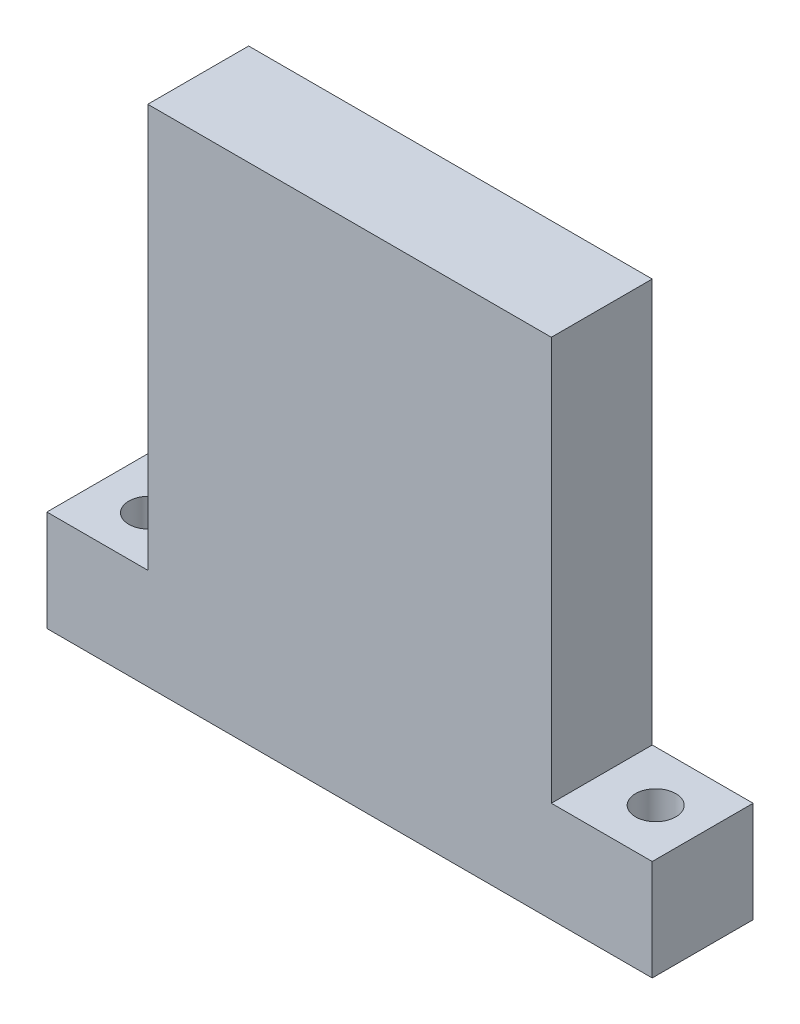
SolidWorks part; units mm, degrees
ref_plane "Front Plane" through (0, 0, 0) normal (0, 0, 1) x (1, 0, 0)
ref_plane "Top Plane" through (0, 0, 0) normal (0, 1, 0) x (1, 0, 0)
ref_plane "Right Plane" through (0, 0, 0) normal (1, 0, 0) x (0, 0, -1)
sketch "Sketch1" plane through (0, 0, 0) normal (0, 1, 0) x (1, 0, 0)
  line L1 (-30, 5) -> (30, 5)
  line L2 (-30, 5) -> (-30, -5)
  line L3 (-30, -5) -> (30, -5)
  line L4 (30, 5) -> (30, -5)
  line L5 (-30, 5) -> (30, -5) construction
  line L6 (-30, -5) -> (30, 5) construction
  point P0 (0, 0)
  dimension "D1" = 10
  dimension "D2" = 60
extrude "Boss-Extrude1" add sketch "Sketch1" along normal blind 10
sketch "Sketch2" plane through (0, 10, 0) normal (0, 1, 0) x (1, 0, 0)
  line L0 (-30, -5) -> (30, -5) construction
  line L1 (-20, 5) -> (20, 5)
  line L2 (-20, 5) -> (-20, -5)
  line L3 (-20, -5) -> (20, -5)
  line L4 (20, 5) -> (20, -5)
  line L5 (-20, 5) -> (20, -5) construction
  line L6 (-20, -5) -> (20, 5) construction
  point P0 (0, 0)
  dimension "D1" = 40
extrude "Boss-Extrude2" add sketch "Sketch2" along normal blind 40
sketch "Sketch3" plane through (0, 0, -5) normal (0, 0, -1) x (-1, 0, 0)
  line L0 (0, 0) -> (0, 30) construction
  circle A0 centre (0, 30) radius 11
  dimension "D1" = 22
extrude "Cut-Extrude1" cut sketch "Sketch3" against normal blind 8 contours A0
sketch "Sketch5" plane through (0, 10, 0) normal (0, 1, 0) x (1, 0, 0)
  circle A0 centre (-24.8797, 0) radius 2
  circle A1 centre (25.343, 0) radius 2
extrude "Cut-Extrude2" cut sketch "Sketch5" against normal blind 45
